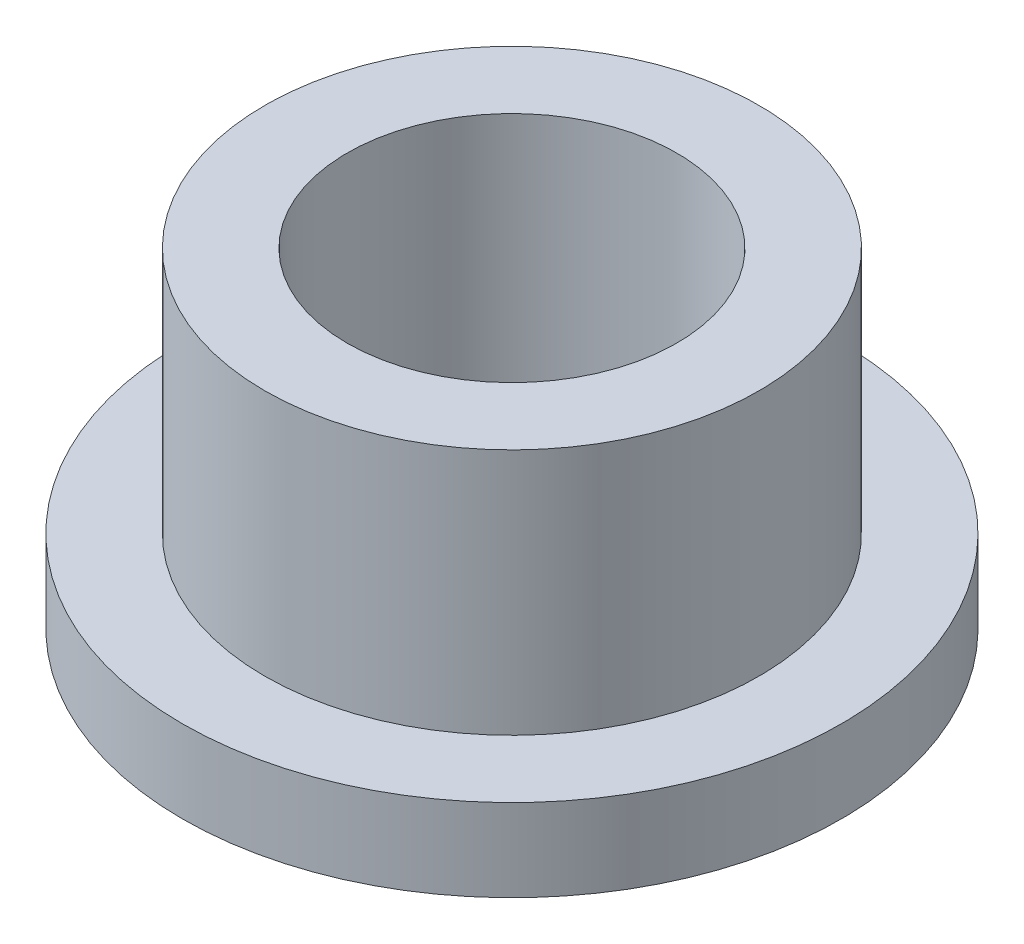
SolidWorks part; units mm, degrees
ref_plane "Front Plane" through (0, 0, 0) normal (0, 0, 1) x (1, 0, 0)
ref_plane "Top Plane" through (0, 0, 0) normal (0, 1, 0) x (1, 0, 0)
ref_plane "Right Plane" through (0, 0, 0) normal (1, 0, 0) x (0, 0, -1)
sketch "Sketch1" plane through (0, 0, 0) normal (0, 1, 0) x (1, 0, 0)
  circle A0 centre (0, 0) radius 12.7
  dimension "D1" = 25.4
extrude "Boss-Extrude1" add sketch "Sketch1" along normal blind 3.175
sketch "Sketch2" plane through (0, 3.175, 0) normal (0, 1, 0) x (1, 0, 0)
  circle A0 centre (0, 0) radius 9.525
  dimension "D1" = 19.05
extrude "Boss-Extrude2" add sketch "Sketch2" along normal offset from surface (9.525 mm away) 12.7 up to face at (0, 0, 12.7)
sketch "Sketch3" plane through (0, 12.7, 0) normal (0, 1, 0) x (1, 0, 0)
  circle A0 centre (0, 0) radius 6.35
  dimension "D1" = 12.7
extrude "Cut-Extrude1" cut sketch "Sketch3" against normal through all
